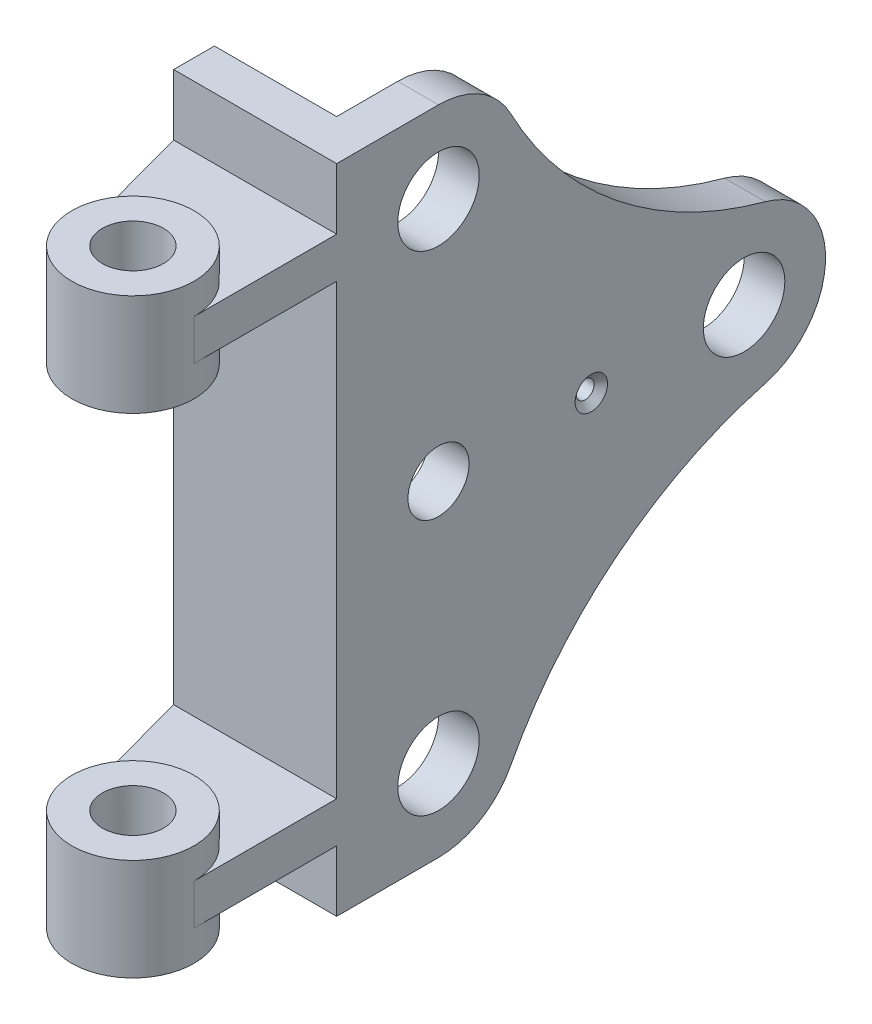
SolidWorks part; units mm, degrees
ref_plane "Plane1" through (0, 0, 0) normal (0, 0, 1) x (1, 0, 0)
ref_plane "Plane2" through (0, 0, 0) normal (0, 1, 0) x (1, 0, 0)
ref_plane "Plane3" through (0, 0, 0) normal (1, 0, 0) x (0, 0, -1)
sketch "Sketch2" plane through (0, 0, 0) normal (1, 0, 0) x (0, 0, -1)
  line L0 (0, 0) -> (0, 101.6)
  line L1 (0, 0) -> (15.875, 0)
  line L2 (0, 50.8) -> (-20.5162, 50.8) construction
  line L3 (0, 101.6) -> (15.875, 101.6)
  arc A0 (66.8019, 63.0633) -> (66.8019, 38.5367) centre (63.5, 50.8) cw
  arc A1 (15.875, 0) -> (27.1144, 6.7867) centre (15.875, 12.7) ccw
  arc A2 (27.1144, 6.7867) -> (66.8019, 38.5367) centre (83.3112, -22.7796) cw
  arc A3 (27.1144, 94.8133) -> (66.8019, 63.0633) centre (83.3112, 124.3796) ccw
  arc A4 (15.875, 101.6) -> (27.1144, 94.8133) centre (15.875, 88.9) cw
  dimension "D1" = 12.7
  dimension "D2" = 12.7
  dimension "D3" = 63.5
  dimension "D6" = 15.875
  dimension "D4" = 101.6
  dimension "D5" = 63.5
extrude "Base-Extrude" add sketch "Sketch2" along normal blind 6.35
sketch "Sketch4" plane through (6.35, 0, 0) normal (1, 0, 0) x (0, 0, -1)
  circle A0 centre (63.5, 50.8) radius 6.35
  circle A1 centre (15.875, 88.9) radius 6.35
  circle A2 centre (15.875, 12.7) radius 6.35
  circle A3 centre (15.875, 50.8) radius 4.7625
  dimension "D1" = 12.7
  dimension "D2" = 9.525
extrude "Cut-Extrude1" cut sketch "Sketch4" against normal through all
sketch "Sketch3" plane through (0, 0, 0) normal (0, 0, 1) x (1, 0, 0)
  line L0 (6.35, 101.6) -> (6.35, 0) construction
  line L1 (6.35, 0) -> (-19.05, 0)
  line L2 (6.35, 0) -> (6.35, 101.6)
  line L3 (6.35, 101.6) -> (-19.05, 101.6)
  line L4 (-19.05, 0) -> (-19.05, 101.6)
  line L5 (6.35, 101.6) -> (0, 101.6) construction
  line L6 (6.35, 0) -> (0, 0) construction
  dimension "D1" = 25.4
extrude "Boss-Extrude1" add sketch "Sketch3" against normal blind 6.35
ref_plane "Plane4" through (0, 88.9, 0) normal (0, 1, 0) x (-1, 0, 0)
sketch "Sketch5" plane through (0, 88.9, 0) normal (0, 1, 0) x (-1, 0, 0)
  line L0 (-6.35, 0) -> (19.05, 0) construction
  line L1 (19.05, 0) -> (-6.35, 0)
  line L2 (12.3699, 24.7107) -> (19.05, 0)
  line L3 (0, -6.35) -> (19.05, -6.35) construction
  line L4 (-6.35, 0) -> (-6.35, 22.225)
  line L5 (-6.35, -15.875) -> (-6.35, 0) construction
  arc A0 (-6.35, 22.225) -> (12.3699, 24.7107) centre (3.175, 22.225) cw
  dimension "D1" = 19.05
  dimension "D2" = 28.575
extrude "Boss-Extrude2" add sketch "Sketch5" along normal mid plane 6.35
sketch "Sketch6" plane through (0, 88.9, 0) normal (0, 1, 0) x (-1, 0, 0)
  circle A0 centre (3.175, 22.225) radius 9.525
  arc A3 (12.3699, 24.7107) -> (-6.35, 22.225) centre (3.175, 22.225) ccw construction
extrude "Boss-Extrude3" add sketch "Sketch6" along normal mid plane 15.875
sketch "Sketch7" plane through (0, 96.8375, 0) normal (0, 1, 0) x (-1, 0, 0)
  circle A0 centre (3.175, 22.225) radius 4.7625
  dimension "D1" = 9.525
extrude "Cut-Extrude2" cut sketch "Sketch7" against normal through all
fillet "Fillet1" [suppressed] radius 1.5875
fillet "Fillet2" [suppressed] radius 1.5875
ref_plane "Plane5" through (0, 50.8, 0) normal (0, 1, 0) x (-1, 0, 0)
mirror "Mirror2" about plane through (0, 50.8, 0) normal (0, 1, 0) of "Boss-Extrude2", "Boss-Extrude3", "Cut-Extrude2", "Fillet1", "Fillet2"
fillet "Fillet3" [suppressed] radius 1.5875
fillet "Fillet4" [suppressed] radius 1.5875
hole_wizard "CSK for #3 Flat Head Machine Screw (100)1" positions "Sketch9" profile "Sketch8" countersink size "#3" standard "Ansi Inch"
sketch "Sketch9" plane through (6.35, 0, 0) normal (1, 0, 0) x (0, 0, -1)
  line L0 (15.875, 50.8) -> (63.5, 50.8) construction
  point P0 (39.6875, 50.8)
sketch "Sketch8" plane through (6.35, 50.8, -39.6875) normal (0, 1, 0) x (0, 0, -1)
  line L0 (0, 0) -> (0, 5.6019)
  line L1 (0, 5.6019) -> (1.397, 4.7625)
  line L2 (1.397, 4.7625) -> (1.397, 0.9484)
  line L3 (1.397, 0.9484) -> (2.5273, 0)
  line L5 (2.5273, 0) -> (0, 0)
  line L6 (-1.397, 0.9484) -> (-2.5273, 0) construction
  line L10 (0, 5.6019) -> (-1.397, 4.7625) construction
  line L11 (0, -6.35) -> (0, 107.95) construction
  dimension "Hole Dia." = 2.794
  dimension "Hole Depth" = 4.7625
  dimension "Near C'Sink Dia." = 5.0546
  dimension "Near C'Sink Angle" = 100
  dimension "Drill Angle" = 118
